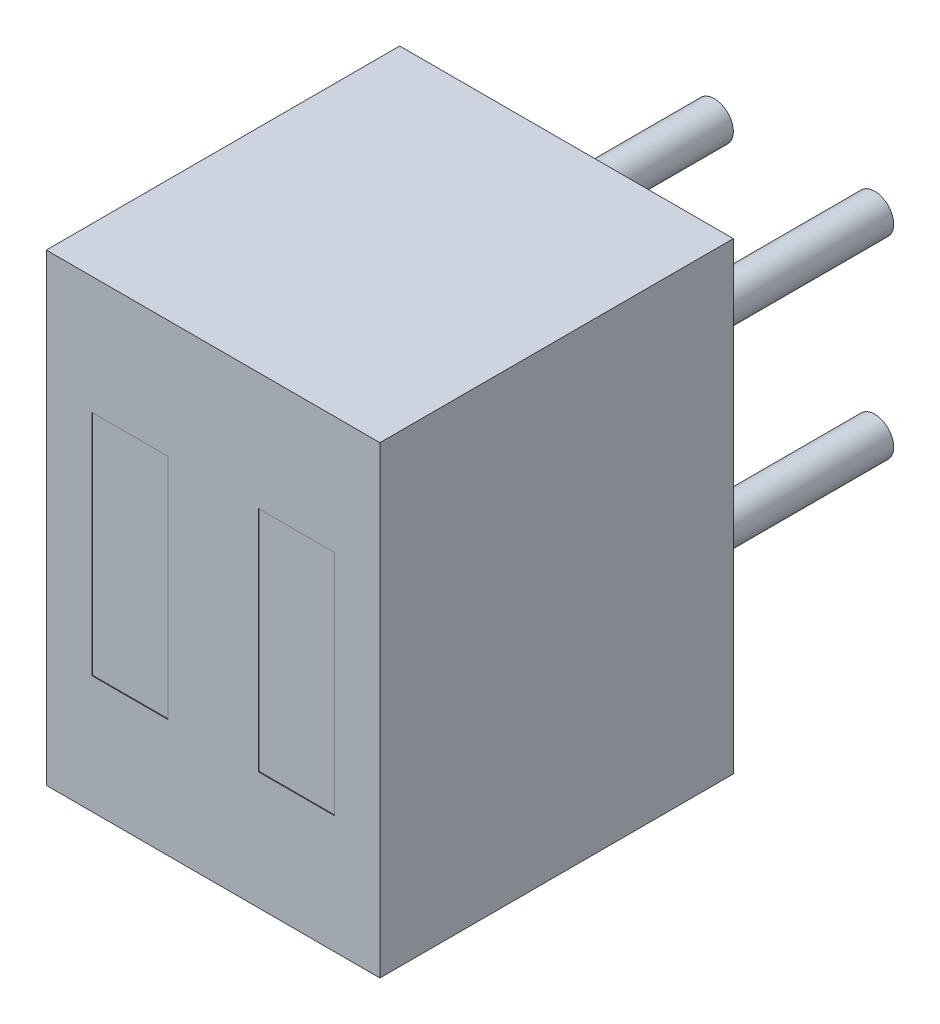
SolidWorks part; units mm, degrees
other "Детальный элемент1"
ref_plane "Спереди" through (0, 0, 0) normal (0, 0, 1) x (1, 0, 0)
ref_plane "Сверху" through (0, 0, 0) normal (0, 1, 0) x (1, 0, 0)
ref_plane "Справа" through (0, 0, 0) normal (1, 0, 0) x (0, 0, -1)
sketch "Эскиз1" plane through (0, 0, 0) normal (0, 0, 1) x (1, 0, 0)
  line L1 (0, 0) -> (4.39, 0)
  line L2 (0, 0) -> (0, 6.1)
  line L3 (0, 6.1) -> (4.39, 6.1)
  line L4 (4.39, 0) -> (4.39, 6.1)
  dimension "D1" = 4.39
  dimension "D2" = 6.1
extrude "Бобышка-Вытянуть1" add sketch "Эскиз1" along normal blind 4.65
sketch "Эскиз2" plane through (0, 0, 4.65) normal (0, 0, 1) x (1, 0, 0)
  line L0 (4.39, 6.1) -> (0, 6.1) construction
  line L1 (0.6, 1.55) -> (1.6, 1.55)
  line L2 (0.6, 1.55) -> (0.6, 4.55)
  line L3 (0.6, 4.55) -> (1.6, 4.55)
  line L4 (1.6, 1.55) -> (1.6, 4.55)
  line L5 (2.79, 1.55) -> (3.79, 1.55)
  line L6 (2.79, 1.55) -> (2.79, 4.55)
  line L7 (2.79, 4.55) -> (3.79, 4.55)
  line L8 (3.79, 1.55) -> (3.79, 4.55)
  line L9 (0, 6.1) -> (0, 0) construction
  line L10 (4.39, 0) -> (4.39, 6.1) construction
  dimension "D1" = 1
  dimension "D2" = 3
  dimension "D3" = 1.55
  dimension "D4" = 0.6
  dimension "D5" = 0.6
extrude "Вырез-Вытянуть1" cut sketch "Эскиз2" against normal blind 0.01
sketch "Эскиз3" plane through (0, 0, 0) normal (0, 0, 1) x (1, 0, 0)
  line L0 (0, 6.1) -> (0, 0) construction
  line L1 (4.39, 0) -> (4.39, 6.1) construction
  circle A0 centre (1.14, 1.78) radius 0.25
  circle A1 centre (3.25, 1.78) radius 0.25
  circle A2 centre (3.25, 4.32) radius 0.25
  circle A3 centre (1.14, 4.32) radius 0.25
  point P8 (0, 0)
  point P10 (0, 0)
  point P11 (0, 0)
  point P12 (0, 0)
  point P13 (0, 0)
  point P15 (0, 0)
  point P18 (0, 0)
  dimension "D1" = 0.5
  dimension "D2" = 1.78
  dimension "D3" = 1.78
  dimension "D4" = 1.14
  dimension "D5" = 1.14
extrude "Бобышка-Вытянуть2" add sketch "Эскиз3" against normal blind 3
